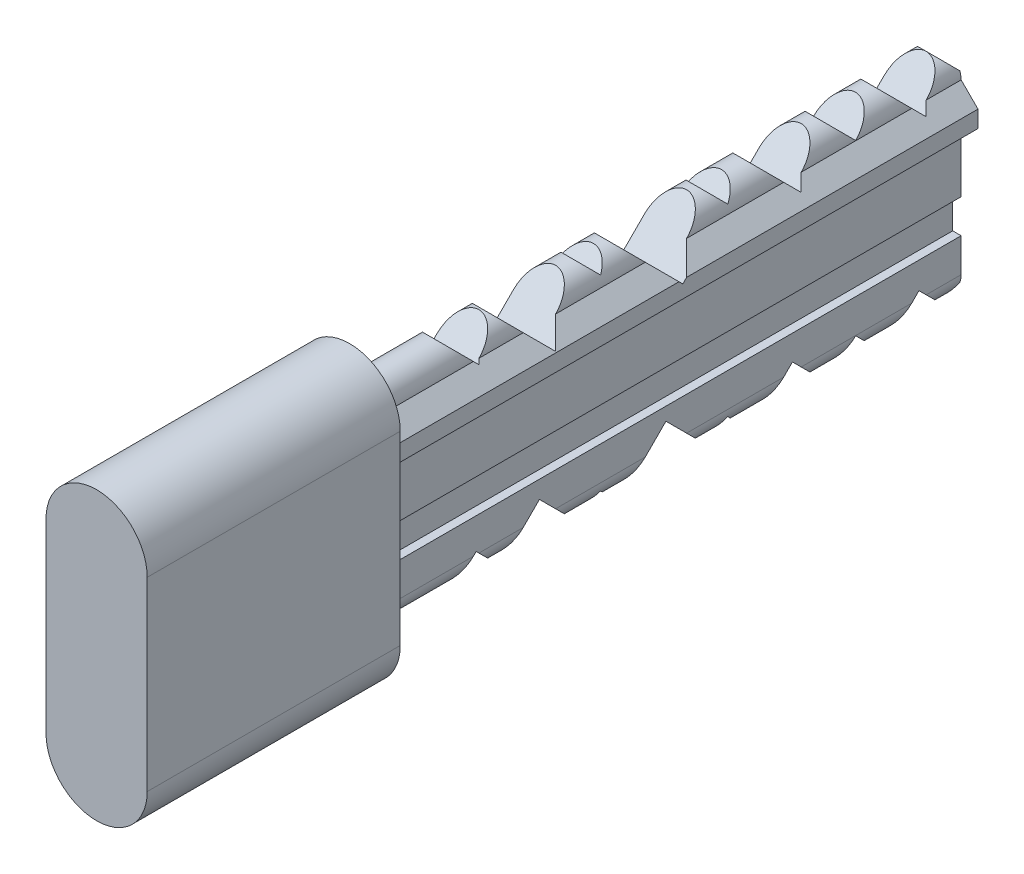
SolidWorks part; units mm, degrees
ref_plane "Płaszczyzna przednia" through (0, 0, 0) normal (0, 0, 1) x (1, 0, 0)
ref_plane "Płaszczyzna górna" through (0, 0, 0) normal (0, 1, 0) x (1, 0, 0)
ref_plane "Płaszczyzna prawa" through (0, 0, 0) normal (1, 0, 0) x (0, 0, -1)
sketch "Szkic1" plane through (0, 0, 0) normal (0, 0, 1) x (1, 0, 0)
  line L0 (1.1183, -7.9284) -> (1.1183, 12.0716) construction
  line L1 (-1.3817, -3.9284) -> (-1.3817, 4.0716)
  line L2 (3.6183, -7.9284) -> (3.6183, -3.9284)
  line L3 (-1.3817, -7.9284) -> (-3.3817, -5.9284)
  line L6 (3.6183, 8.0716) -> (5.6183, 8.0716)
  line L7 (5.6183, 10.0716) -> (5.6183, 8.0716)
  line L10 (-1.3817, -3.9284) -> (-3.3817, -3.9284)
  line L11 (-3.3817, -5.9284) -> (-3.3817, -3.9284)
  line L12 (3.6183, 12.0716) -> (5.6183, 10.0716)
  line L13 (-1.3817, 8.0716) -> (-1.3817, 12.0716)
  line L14 (3.6183, -3.9284) -> (2.6183, -3.9284)
  line L16 (3.6183, 0.0716) -> (2.6183, 0.0716)
  line L17 (2.6183, -3.9284) -> (2.6183, 0.0716)
  line L18 (-1.3817, 8.0716) -> (-0.3817, 8.0716)
  line L20 (-1.3817, 4.0716) -> (-0.3817, 4.0716)
  line L21 (-0.3817, 8.0716) -> (-0.3817, 4.0716)
  line L22 (3.6183, 0.0716) -> (3.6183, 8.0716)
  arc A0 (-1.3817, -7.9284) -> (3.6183, -7.9284) centre (1.1183, -7.9284) ccw
  arc A1 (3.6183, 12.0716) -> (-1.3817, 12.0716) centre (1.1183, 12.0716) ccw
  point P2 (0, 0)
  dimension "D1" = 4
  dimension "D10" = 2.5
  dimension "D11" = 2.5
  dimension "D2" = 2
  dimension "D3" = 2
  dimension "D4" = 4
  dimension "D5" = 4
  dimension "D6" = 4
  dimension "D7" = 1
  dimension "D8" = 1
  dimension "D9" = 5
  dimension "D12" = 4
  dimension "D13" = 20
  dimension "D14" = 0
extrude "key-main-extursion" add sketch "Szkic1" against normal blind 70
sketch "key-handle-sketch" plane through (0, 0, 0) normal (0, 0, 1) x (1, 0, 0)
  line L0 (1.1183, -9.253) -> (1.1183, 12.747) construction
  line L3 (-4.8817, -9.253) -> (-4.8817, 12.747)
  line L4 (7.1183, -9.253) -> (7.1183, 12.747)
  line L16 (3.6183, -7.9284) -> (3.6183, -3.9284)
  line L17 (3.6183, -3.9284) -> (2.6183, -3.9284)
  line L18 (2.6183, -3.9284) -> (2.6183, 0.0716)
  line L19 (2.6183, 0.0716) -> (3.6183, 0.0716)
  line L20 (3.6183, 0.0716) -> (3.6183, 8.0716)
  line L21 (3.6183, 8.0716) -> (5.6183, 8.0716)
  line L22 (5.6183, 8.0716) -> (5.6183, 10.0716)
  line L23 (5.6183, 10.0716) -> (3.6183, 12.0716)
  line L24 (-1.3817, 12.0716) -> (-1.3817, 8.0716)
  line L25 (-1.3817, 8.0716) -> (-0.3817, 8.0716)
  line L26 (-0.3817, 8.0716) -> (-0.3817, 4.0716)
  line L27 (-0.3817, 4.0716) -> (-1.3817, 4.0716)
  line L28 (-1.3817, 4.0716) -> (-1.3817, -3.9284)
  line L29 (-1.3817, -3.9284) -> (-3.3817, -3.9284)
  line L30 (-3.3817, -3.9284) -> (-3.3817, -5.9284)
  line L31 (-3.3817, -5.9284) -> (-1.3817, -7.9284)
  line L32 (3.6183, -7.9284) -> (3.6183, -3.9284)
  line L33 (3.6183, -3.9284) -> (2.6183, -3.9284)
  line L34 (2.6183, -3.9284) -> (2.6183, 0.0716)
  line L35 (2.6183, 0.0716) -> (3.6183, 0.0716)
  line L36 (3.6183, 0.0716) -> (3.6183, 8.0716)
  line L37 (3.6183, 8.0716) -> (5.6183, 8.0716)
  line L38 (5.6183, 8.0716) -> (5.6183, 10.0716)
  line L39 (5.6183, 10.0716) -> (3.6183, 12.0716)
  line L40 (-1.3817, 12.0716) -> (-1.3817, 8.0716)
  line L41 (-1.3817, 8.0716) -> (-0.3817, 8.0716)
  line L42 (-0.3817, 8.0716) -> (-0.3817, 4.0716)
  line L43 (-0.3817, 4.0716) -> (-1.3817, 4.0716)
  line L44 (-1.3817, 4.0716) -> (-1.3817, -3.9284)
  line L45 (-1.3817, -3.9284) -> (-3.3817, -3.9284)
  line L46 (-3.3817, -3.9284) -> (-3.3817, -5.9284)
  line L47 (-3.3817, -5.9284) -> (-1.3817, -7.9284)
  arc A2 (-1.3817, -7.9284) -> (3.6183, -7.9284) centre (1.1183, -7.9284) ccw
  arc A3 (3.6183, 12.0716) -> (-1.3817, 12.0716) centre (1.1183, 12.0716) ccw
  arc A4 (-1.3817, -7.9284) -> (3.6183, -7.9284) centre (1.1183, -7.9284) ccw
  arc A5 (3.6183, 12.0716) -> (-1.3817, 12.0716) centre (1.1183, 12.0716) ccw
  arc A6 (-4.8817, -9.253) -> (7.1183, -9.253) centre (1.1183, -9.253) ccw
  arc A7 (7.1183, 12.747) -> (-4.8817, 12.747) centre (1.1183, 12.747) ccw
  point P7 (1.1183, 1.747)
  point P11 (1.1183, 1.747)
  dimension "D2" = 22
  dimension "D3" = 12
  dimension "D1" = 0
extrude "key-handle" add sketch "key-handle-sketch" along normal blind 30
sketch "Szkic5" plane through (-3.75, 0, 0) normal (-1, 0, 0) x (0, 0, 1)
  line L0 (-65, -10.4284) -> (-57.5, -10.4284) construction
  line L1 (-70, 14.5716) -> (0, 14.5716)
  line L2 (-70, 14.5716) -> (-70, 12.9303)
  line L3 (-70, -10.4284) -> (0, -10.4284)
  line L5 (-65, -7.0697) -> (-68.3588, -10.4284)
  line L6 (-65, -7.0697) -> (-61.6412, -10.4284)
  line L7 (-65, -7.0697) -> (-65, -10.4284) construction
  line L8 (-68.3588, -10.4284) -> (-70, -8.7872)
  line L9 (-59.9749, -10.4284) -> (-57.5, -7.9536)
  line L10 (-57.5, -7.9536) -> (-55.0251, -10.4284)
  line L11 (-57.5, -7.9536) -> (-57.5, -10.4284) construction
  line L12 (-53.5355, -10.4284) -> (-50, -6.8929)
  line L13 (-50, -6.8929) -> (-46.4645, -10.4284)
  line L14 (-50, -6.8929) -> (-50, -10.4284) construction
  line L15 (-44.091, -10.4284) -> (-42.5, -8.8374)
  line L16 (-42.5, -8.8374) -> (-40.909, -10.4284)
  line L17 (-42.5, -8.8374) -> (-42.5, -10.4284) construction
  line L18 (-39.9497, -10.4284) -> (-35, -5.4787)
  line L19 (-35, -5.4787) -> (-30.0503, -10.4284)
  line L20 (-35, -5.4787) -> (-35, -10.4284) construction
  line L21 (-28.9142, -10.4284) -> (-27.5, -9.0142)
  line L22 (-27.5, -9.0142) -> (-26.0858, -10.4284)
  line L23 (-27.5, -9.0142) -> (-27.5, -10.4284) construction
  line L24 (-24.4194, -10.4284) -> (-20, -6.009)
  line L25 (-20, -6.009) -> (-15.5806, -10.4284)
  line L26 (-20, -6.009) -> (-20, -10.4284) construction
  line L27 (-15.3284, -10.4284) -> (-12.5, -7.6)
  line L28 (-12.5, -7.6) -> (-9.6716, -10.4284)
  line L29 (-12.5, -7.6) -> (-12.5, -10.4284) construction
  line L30 (-70, 0) -> (36.1836, 0) construction
  line L32 (-65, 14.5716) -> (-57.5, 14.5716) construction
  line L33 (-70, 14.5716) -> (0, 14.5716)
  line L34 (-70, 14.5716) -> (-70, 12.9303)
  line L35 (-70, -10.4284) -> (0, -10.4284)
  line L37 (-68.3588, 14.5716) -> (-65, 11.2128)
  line L38 (-65, 11.2128) -> (-61.6412, 14.5716)
  line L39 (-61.6412, 14.5716) -> (-59.9749, 14.5716)
  line L40 (-59.9749, 14.5716) -> (-57.5, 12.0967)
  line L41 (-57.5, 12.0967) -> (-55.0251, 14.5716)
  line L42 (-55.0251, 14.5716) -> (-53.5355, 14.5716)
  line L43 (-53.5355, 14.5716) -> (-50, 11.036)
  line L44 (-50, 11.036) -> (-46.4645, 14.5716)
  line L45 (-46.4645, 14.5716) -> (-44.091, 14.5716)
  line L46 (-44.091, 14.5716) -> (-42.5, 12.9806)
  line L47 (-42.5, 12.9806) -> (-40.909, 14.5716)
  line L48 (-40.909, 14.5716) -> (-39.9497, 14.5716)
  line L49 (-39.9497, 14.5716) -> (-35, 9.6218)
  line L50 (-35, 9.6218) -> (-30.0503, 14.5716)
  line L51 (-30.0503, 14.5716) -> (-28.9142, 14.5716)
  line L52 (-28.9142, 14.5716) -> (-27.5, 13.1574)
  line L53 (-27.5, 13.1574) -> (-26.0858, 14.5716)
  line L54 (-26.0858, 14.5716) -> (-24.4194, 14.5716)
  line L55 (-24.4194, 14.5716) -> (-20, 10.1522)
  line L56 (-20, 10.1522) -> (-15.5806, 14.5716)
  line L57 (-15.5806, 14.5716) -> (-15.3284, 14.5716)
  line L58 (-15.3284, 14.5716) -> (-12.5, 11.7431)
  line L59 (-12.5, 11.7431) -> (-9.6716, 14.5716)
  line L60 (-68.3588, 14.5716) -> (-70, 12.9303)
  line L61 (-65, 11.2128) -> (-65, 14.5716) construction
  line L62 (-57.5, 12.0967) -> (-57.5, 14.5716) construction
  line L63 (-50, 11.036) -> (-50, 14.5716) construction
  line L64 (-42.5, 12.9806) -> (-42.5, 14.5716) construction
  line L65 (-35, 9.6218) -> (-35, 14.5716) construction
  line L66 (-27.5, 13.1574) -> (-27.5, 14.5716) construction
  line L67 (-20, 10.1522) -> (-20, 14.5716) construction
  line L68 (-12.5, 11.7431) -> (-12.5, 14.5716) construction
  line L69 (-70, -8.7872) -> (-70, -10.4284)
  line L70 (-70, 14.5716) -> (0, 14.5716)
  line L71 (-70, 14.5716) -> (-70, 12.9303)
  line L72 (-70, -10.4284) -> (0, -10.4284)
  line L74 (-70, -8.7872) -> (-70, -10.4284)
  line L75 (-70, -8.7872) -> (-70, -10.4284)
  point P6 (-65, -10.4284)
  point P7 (-57.5, -10.4284)
  point P9 (-50, -10.4284)
  point P10 (-42.5, -10.4284)
  point P11 (-35, -10.4284)
  point P12 (-27.5, -10.4284)
  point P13 (-20, -10.4284)
  point P14 (-12.5, -10.4284)
  point P50 (-65, 14.5716)
  point P54 (-57.5, 14.5716)
  point P55 (-50, 14.5716)
  point P56 (-42.5, 14.5716)
  point P57 (-35, 14.5716)
  point P58 (-27.5, 14.5716)
  point P59 (-20, 14.5716)
  point P60 (-12.5, 14.5716)
  dimension "D1" = 5
  dimension "D3" = 7.5
  dimension "D4" = 4.75
  dimension "D5" = 4.75
  dimension "D6" = 3.5
  dimension "D7" = 3.5
  dimension "D8" = 90
  dimension "D9" = 90
  dimension "D10" = 5
  dimension "D11" = 5
  dimension "D12" = 90
  dimension "D13" = 2.25
  dimension "D14" = 2.25
  dimension "D15" = 90
  dimension "D16" = 7
  dimension "D17" = 7
  dimension "D18" = 2
  dimension "D19" = 2
  dimension "D20" = 90
  dimension "D21" = 6.25
  dimension "D22" = 6.25
  dimension "D23" = 90
  dimension "D24" = 4
  dimension "D25" = 4
  dimension "D26" = 90
  dimension "D27" = 45
  dimension "D28" = 5
  dimension "D30" = 7.5
  dimension "D31" = 45
  dimension "D32" = 4.75
  dimension "D33" = 4.75
  dimension "D34" = 90
  dimension "D35" = 90
  dimension "D36" = 90
  dimension "D37" = 90
  dimension "D38" = 90
  dimension "D39" = 90
  dimension "D40" = 90
  dimension "D41" = 90
  dimension "D42" = 4
  dimension "D43" = 4
  dimension "D44" = 6.25
  dimension "D45" = 6.25
  dimension "D46" = 2
  dimension "D47" = 2
  dimension "D48" = 7
  dimension "D49" = 7
  dimension "D50" = 2.25
  dimension "D51" = 2.25
  dimension "D52" = 5
  dimension "D53" = 5
  dimension "D54" = 3.5
  dimension "D55" = 3.5
  dimension "D56" = 0
  dimension "D2" = 8
  dimension "D29" = 8
extrude "key-cut" cut sketch "Szkic5" against normal through all contours L6 L5 L3 | L3 L8 L2 | L10 L9 L3 | L13 L12 L3 | L16 L15 L3 | L19 L18 L3 | L22 L21 L3 | L25 L24 L3 | L28 L27 L3 | L60 L1 L2 | L37 L38 L33 | L40 L41 L33 | L43 L44 L33 | L46 L47 L33 | L49 L50 L33 | L52 L53 L33 | L55 L56 L33 | L58 L59 L33
